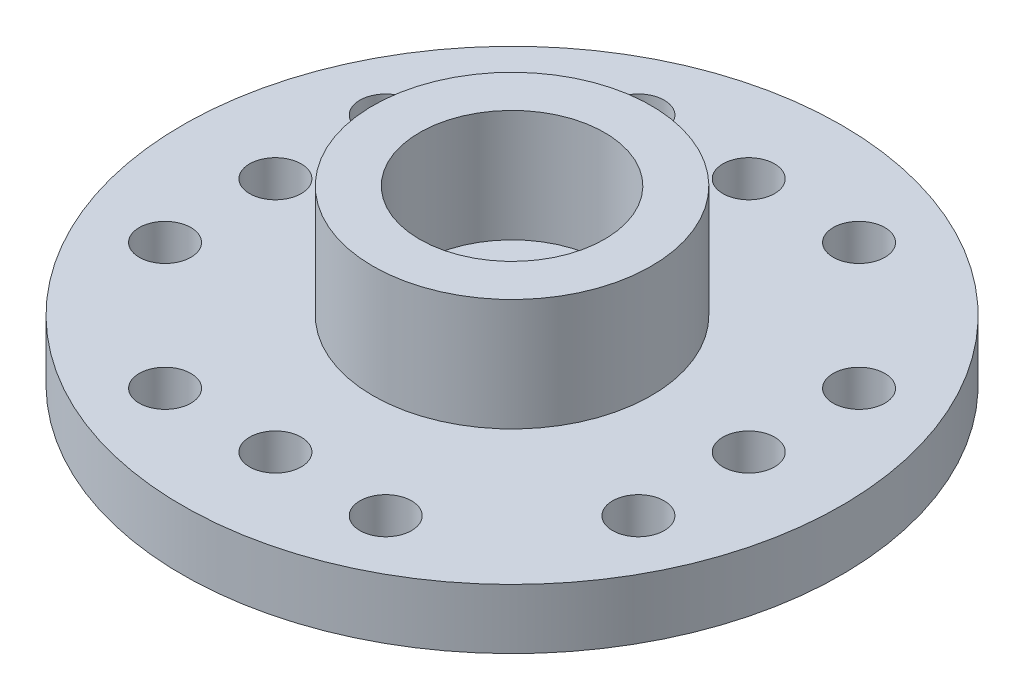
SolidWorks part; units mm, degrees
material "ABS"
ref_plane "Front Plane" through (0, 0, 0) normal (0, 0, 1) x (1, 0, 0)
ref_plane "Top Plane" through (0, 0, 0) normal (0, 1, 0) x (1, 0, 0)
ref_plane "Right Plane" through (0, 0, 0) normal (1, 0, 0) x (0, 0, -1)
sketch "Sketch1" plane through (0, 0, 0) normal (0, 1, 0) x (1, 0, 0)
  circle A0 centre (0, 0) radius 10.4521
  dimension "D1" = 20.9042
extrude "Boss-Extrude1" add sketch "Sketch1" along normal blind 1.9
sketch "Sketch2" plane through (0, 1.9, 0) normal (0, 1, 0) x (1, 0, 0)
  circle A0 centre (0, 0) radius 4.4132
  dimension "D1" = 8.8265
extrude "Boss-Extrude2" add sketch "Sketch2" along normal blind 3.556
sketch "Sketch3" plane through (0, 0, 0) normal (0, -1, 0) x (1, 0, 0)
  line L0 (0, 0) -> (-7.5057, 0) construction
  line L1 (-7.5057, 3.4988) -> (-7.5057, -3.4989) construction
  line L2 (3.4989, 7.5057) -> (-3.4988, 7.5057) construction
  line L3 (7.5057, -3.4989) -> (7.5057, 3.4988) construction
  line L4 (-3.4989, -7.5057) -> (3.4988, -7.5057) construction
  circle A0 centre (0, 0) radius 1.4922
  circle A1 centre (-7.5057, 0) radius 0.8192
  circle A2 centre (-7.5057, 3.4988) radius 0.8192
  circle A3 centre (-7.5057, -3.4989) radius 0.8192
  circle A4 centre (0, 7.5057) radius 0.8192
  circle A5 centre (3.4989, 7.5057) radius 0.8192
  circle A6 centre (-3.4988, 7.5057) radius 0.8192
  circle A7 centre (7.5057, 0) radius 0.8192
  circle A8 centre (7.5057, -3.4989) radius 0.8192
  circle A9 centre (7.5057, 3.4988) radius 0.8192
  circle A10 centre (0, -7.5057) radius 0.8192
  circle A11 centre (-3.4989, -7.5057) radius 0.8192
  circle A12 centre (3.4988, -7.5057) radius 0.8192
  point P9 (-1.4922, 0)
  point P10 (-7.5057, 2.6797)
  point P11 (-6.6865, 0)
  point P12 (-7.5057, -2.6797)
  point P22 (2.6797, 7.5057)
  point P23 (0, 6.6865)
  point P24 (-2.6797, 7.5057)
  point P31 (7.5057, -2.6797)
  point P32 (6.6865, 0)
  point P33 (7.5057, 2.6797)
  point P40 (-2.6797, -7.5057)
  point P41 (0, -6.6865)
  point P42 (2.6797, -7.5057)
  point P43 (0, 0)
  dimension "D1" = 1.6383
  dimension "D2" = 2.9845
  dimension "D3" = 5.1943
  dimension "D4" = 5.3594
  dimension "D5" = 4
extrude "Cut-Extrude1" cut sketch "Sketch3" against normal through all
sketch "Sketch4" plane through (0, 5.456, 0) normal (0, 1, 0) x (1, 0, 0)
  circle A0 centre (0, 0) radius 2.9337
  dimension "D1" = 5.8674
extrude "Cut-Extrude2" cut sketch "Sketch4" against normal up to surface (3.556 mm away) up to face at (7.5057, 1.9, -2.6797)
